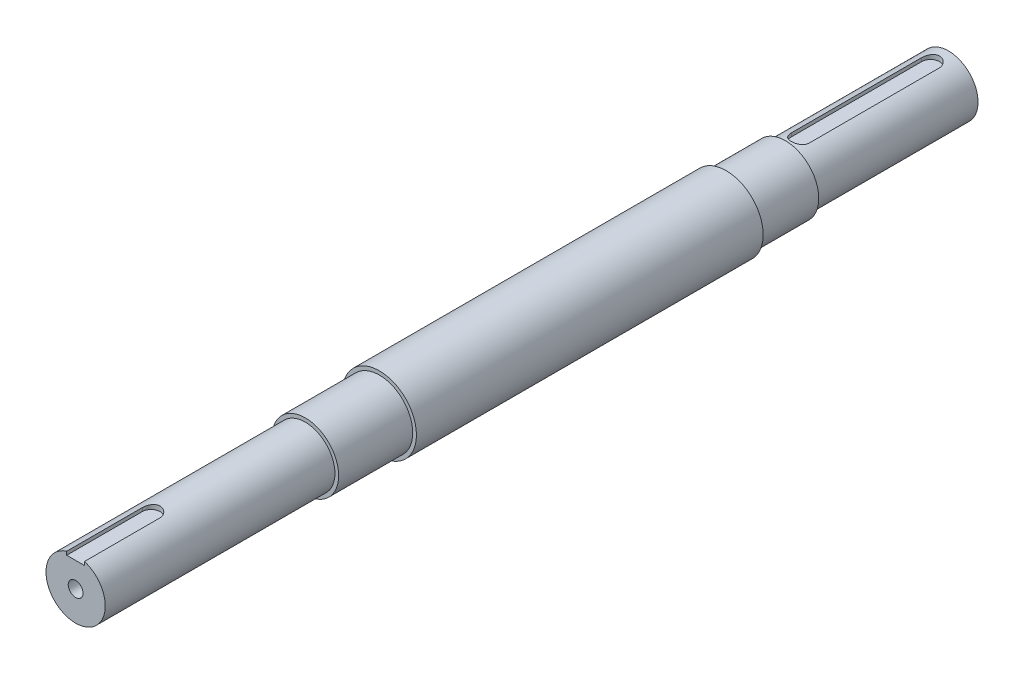
SolidWorks part; units mm, degrees
material "CK-45"
ref_plane "Front Plane" through (0, 0, 0) normal (0, 0, 1) x (1, 0, 0)
ref_plane "Top Plane" through (0, 0, 0) normal (0, 1, 0) x (1, 0, 0)
ref_plane "Right Plane" through (0, 0, 0) normal (1, 0, 0) x (0, 0, -1)
sketch "Sketch1" plane through (0, 0, 0) normal (0, 0, 1) x (1, 0, 0)
  circle A0 centre (0, 0) radius 25
  dimension "D1" = 50
extrude "Boss-Extrude1" add sketch "Sketch1" along normal blind 234
sketch "Sketch2" plane through (0, 0, 0) normal (0, 0, -1) x (-1, 0, 0)
  circle A0 centre (0, 0) radius 22.5
  dimension "D1" = 45
extrude "Boss-Extrude2" add sketch "Sketch2" along normal blind 40
sketch "Sketch3" plane through (0, 0, -40) normal (0, 0, -1) x (-1, 0, 0)
  circle A0 centre (0, 0) radius 20
  dimension "D1" = 40
extrude "Boss-Extrude3" add sketch "Sketch3" along normal blind 110
sketch "Sketch4" plane through (0, 0, 234) normal (0, 0, 1) x (1, 0, 0)
  circle A0 centre (0, 0) radius 22.5
  dimension "D1" = 45
extrude "Boss-Extrude4" add sketch "Sketch4" along normal blind 50
sketch "Sketch5" plane through (0, 0, 284) normal (0, 0, 1) x (1, 0, 0)
  circle A0 centre (0, 0) radius 20
  dimension "D1" = 40
extrude "Boss-Extrude5" add sketch "Sketch5" along normal blind 155
ref_plane "Plane1" through (0, 20, 0) normal (0, 1, 0) x (1, 0, 0)
sketch "Sketch6" plane through (0, 20, 0) normal (0, 1, 0) x (1, 0, 0)
  line L0 (0, -439) -> (0, -388) construction
  line L1 (-6, -439) -> (-6, -388)
  line L2 (6, -439) -> (6, -388)
  line L3 (-20, -439) -> (20, -439) construction
  arc A0 (-6, -439) -> (6, -439) centre (0, -439) ccw
  arc A1 (6, -388) -> (-6, -388) centre (0, -388) ccw
  point P3 (0, -413.5)
  dimension "D1" = 6
  dimension "D2" = 0
  dimension "D3" = 51
extrude "Cut-Extrude1" cut sketch "Sketch6" against normal blind 3.3
sketch "Sketch7" plane through (0, 0, 439) normal (0, 0, 1) x (1, 0, 0)
  circle A0 centre (0, 0) radius 5
  dimension "D1" = 10
extrude "Cut-Extrude2" cut sketch "Sketch7" against normal blind 45
sketch "Sketch8" plane through (0, 20, 0) normal (0, 1, 0) x (1, 0, 0)
  line L0 (0, 138) -> (0, 50) construction
  line L1 (6, 138) -> (6, 50)
  line L2 (-6, 138) -> (-6, 50)
  line L3 (20, 150) -> (-20, 150) construction
  arc A0 (6, 138) -> (-6, 138) centre (0, 138) ccw
  arc A1 (-6, 50) -> (6, 50) centre (0, 50) ccw
  point P3 (0, 94)
  dimension "D1" = 6
  dimension "D3" = 12
  dimension "D2" = 88
extrude "Cut-Extrude3" cut sketch "Sketch8" against normal blind 3.3
hole_wizard "Ø10.0mm Dowel Hole1" positions "Sketch12" profile "Sketch14" hole size "Ø10.0" standard "ANSI Metric"
sketch "Sketch12" plane through (0, 0, -150) normal (0, 0, -1) x (-1, 0, 0)
  point P0 (0, 0)
sketch "Sketch14" plane through (0, 0, -150) normal (1, 0, 0) x (0, 1, 0)
  line L0 (0, 0) -> (0, 48.0043)
  line L1 (0, 48.0043) -> (5, 45)
  line L2 (5, 45) -> (5, 0)
  line L5 (5, 0) -> (0, 0)
  line L10 (0, 48.0043) -> (-5, 45) construction
  line L11 (0, -6.35) -> (0, 107.95) construction
  dimension "Hole Dia." = 10
  dimension "Hole Depth" = 45
  dimension "Drill Angle" = 118
